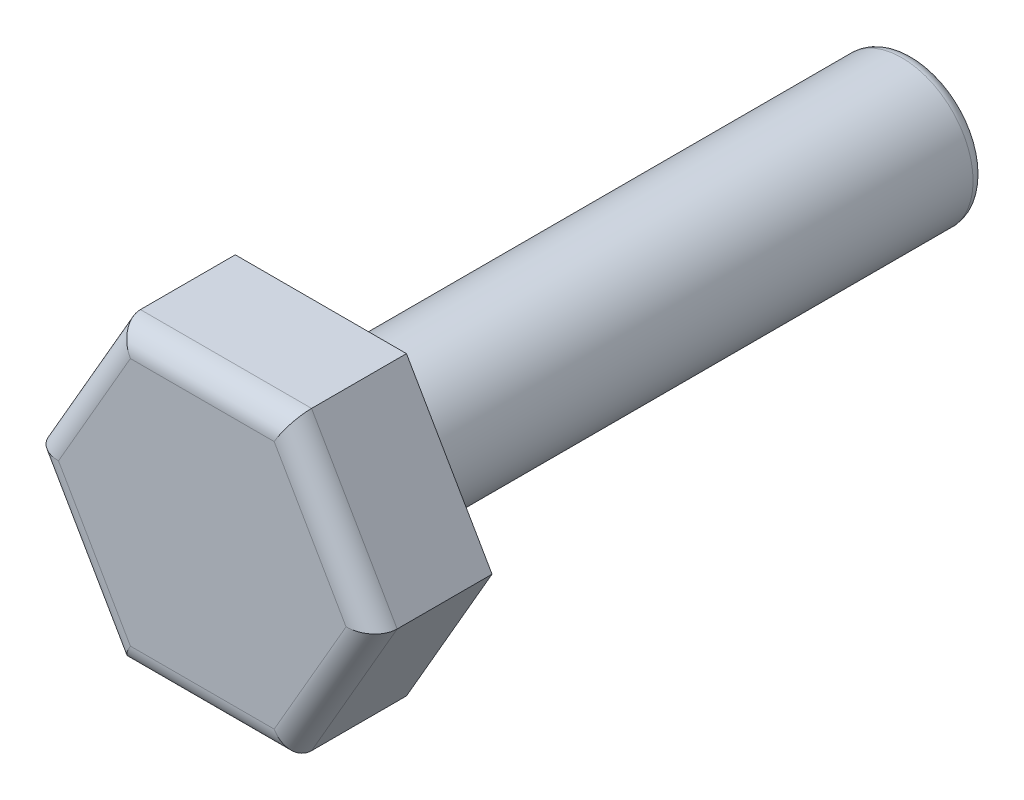
SolidWorks part; units mm, degrees
ref_plane "前视基准面" through (0, 0, 0) normal (0, 0, 1) x (1, 0, 0)
ref_plane "上视基准面" through (0, 0, 0) normal (0, 1, 0) x (1, 0, 0)
ref_plane "右视基准面" through (0, 0, 0) normal (1, 0, 0) x (0, 0, -1)
sketch "草图1" plane through (0, 0, 0) normal (0, 0, 1) x (1, 0, 0)
  circle A0 centre (0, 0) radius 6
  dimension "D1" = 12
extrude "凸台-拉伸1" add sketch "草图1" along normal blind 60
sketch "草图3" plane through (0, 0, 60) normal (0, 0, 1) x (1, 0, 0)
  line L1 (7.2169, -12.5) -> (14.4338, 0)
  line L2 (14.4338, 0) -> (7.2169, 12.5)
  line L3 (7.2169, 12.5) -> (-7.2169, 12.5)
  line L4 (-7.2169, 12.5) -> (-14.4338, 0)
  line L5 (-14.4338, 0) -> (-7.2169, -12.5)
  line L6 (-7.2169, -12.5) -> (7.2169, -12.5)
  circle A0 centre (0, 0) radius 12.5 construction
  dimension "D1" = 25
extrude "凸台-拉伸2" add sketch "草图3" against normal blind 10
fillet "圆角1" radius 2 6 edges at (10.8253, -6.25, 60) (0, -12.5, 60) (-10.8253, -6.25, 60) (-10.8253, 6.25, 60) (0, 12.5, 60) (10.8253, 6.25, 60)
fillet "圆角2" radius 1 1 edges at (6, 0, 0)
